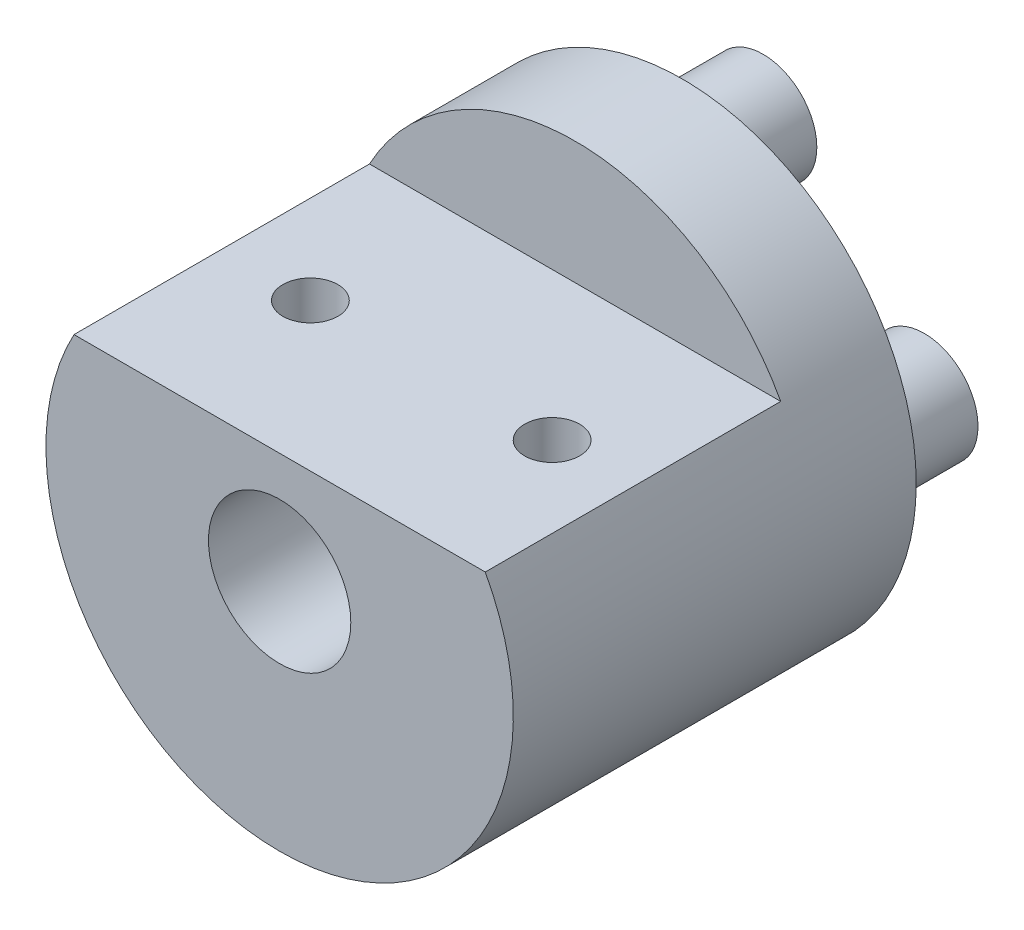
SolidWorks part; units mm, degrees
ref_plane "Front Plane" through (0, 0, 0) normal (0, 0, 1) x (1, 0, 0)
ref_plane "Top Plane" through (0, 0, 0) normal (0, 1, 0) x (1, 0, 0)
ref_plane "Right Plane" through (0, 0, 0) normal (1, 0, 0) x (0, 0, -1)
sketch "Sketch1" plane through (0, 0, 0) normal (0, 0, 1) x (1, 0, 0)
  circle A0 centre (0, 0) radius 8.7
  dimension "D1" = 17.4
extrude "Boss-Extrude1" add sketch "Sketch1" along normal blind 15 contours A0
sketch "Sketch2" plane through (0, 0, 15) normal (0, 0, 1) x (1, 0, 0)
  line L1 (-7.6555, 8.7) -> (9.3445, 8.7)
  line L2 (-7.6555, 8.7) -> (-7.6555, 4.1331)
  line L3 (-7.6555, 4.1331) -> (9.3445, 4.1331)
  line L4 (9.3445, 8.7) -> (9.3445, 4.1331)
  circle A0 centre (0, 0) radius 8.7 construction
  dimension "D1" = 17
sketch "Sketch4" plane through (0, 0, 0) normal (0, 0, -1) x (-1, 0, 0)
  circle A0 centre (0, 6) radius 2
  circle A1 centre (6, 0) radius 2
  circle A2 centre (0, -6) radius 2
  circle A3 centre (-6, 0) radius 2
  dimension "D1" = 4
  dimension "D2" = 6
  dimension "D3" = 6
  dimension "D4" = 6
  dimension "D5" = 6
sketch "Sketch5" plane through (0, 0, 0) normal (0, 0, -1) x (-1, 0, 0)
  circle A0 centre (0, 0) radius 1.75
  dimension "D1" = 3.5
extrude "Cut-Extrude1" cut sketch "Sketch5" against normal through all
sketch "Sketch6" plane through (0, 0, 15) normal (0, 0, 1) x (1, 0, 0)
  circle A0 centre (0, 0) radius 2.65
  dimension "D1" = 5.3
extrude "Cut-Extrude3" cut sketch "Sketch6" against normal blind 6.4
extrude "Cut-Extrude4" cut sketch "Sketch2" against normal blind 11 contours L1 L4 L3 L2
fillet "Fillet1" radius 0.3 1 edges at (1.75, 0, 8.6)
hole_wizard "Tap Drill for M2.5x0.45 Tap2" positions "Sketch11" profile "Sketch12" hole size "M2.5x0.45" standard "ANSI Metric" end condition through all
sketch "Sketch11" plane through (0, 4.1331, 0) normal (0, 1, 0) x (1, 0, 0)
  line L0 (-7.6555, -15) -> (7.6555, -15) construction
  line L1 (-7.6555, -4) -> (-7.6555, -15) construction
  point P0 (-4.3555, -9.5)
  point P2 (4.6445, -9.5)
  dimension "D1" = 9
  dimension "D2" = 5.5
  dimension "D3" = 3.3
sketch "Sketch12" plane through (-4.3555, 4.1331, 9.5) normal (1, 0, 0) x (0, 0, 1)
  line L0 (0, 0) -> (0, 12.8331)
  line L1 (0, 12.8331) -> (1.025, 12.8331)
  line L2 (1.025, 12.8331) -> (1.025, 0)
  line L5 (1.025, 0) -> (0, 0)
  line L11 (0, -6.35) -> (0, 107.95) construction
  dimension "Thru Hole Dia." = 2.05
  dimension "Thru Hole Depth" = 12.8331
extrude "Boss-Extrude2" add sketch "Sketch4" along normal blind 3
